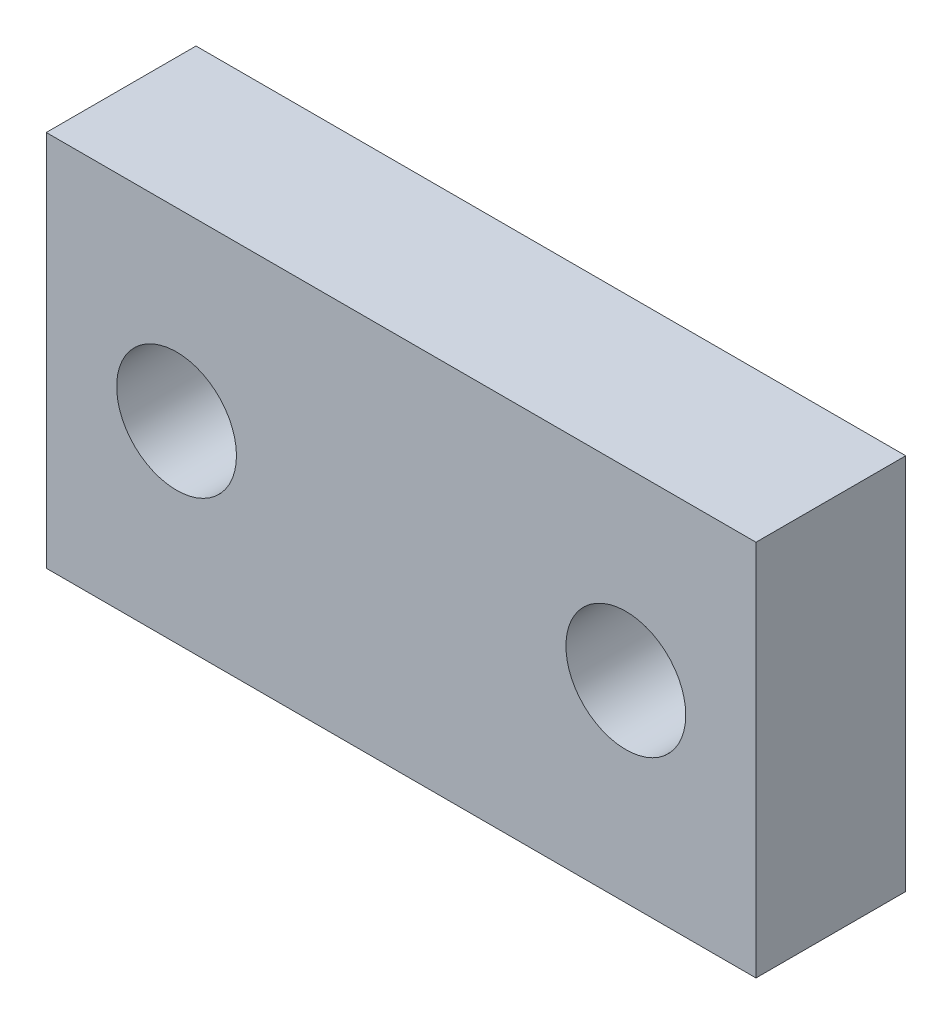
SolidWorks part; units mm, degrees
ref_plane "Plan de face" through (0, 0, 0) normal (0, 0, 1) x (1, 0, 0)
ref_plane "Plan de dessus" through (0, 0, 0) normal (0, 1, 0) x (1, 0, 0)
ref_plane "Plan de droite" through (0, 0, 0) normal (1, 0, 0) x (0, 0, -1)
sketch "Esquisse1" plane through (0, 0, 0) normal (0, 0, 1) x (1, 0, 0)
  line L0 (5.8555, 18.596) -> (5.8555, 5.996)
  line L1 (-17.8397, 18.596) -> (5.8555, 18.596)
  line L2 (-17.8397, 5.996) -> (5.8555, 5.996)
  line L3 (-17.8397, 18.596) -> (-17.8397, 5.996)
  circle A0 centre (-13.4897, 12.426) radius 2
  circle A1 centre (1.5103, 12.426) radius 2
  dimension "D1" = 4
  dimension "D2" = 4.35
extrude "Boss.-Extru.1" add sketch "Esquisse1" along normal blind 5
